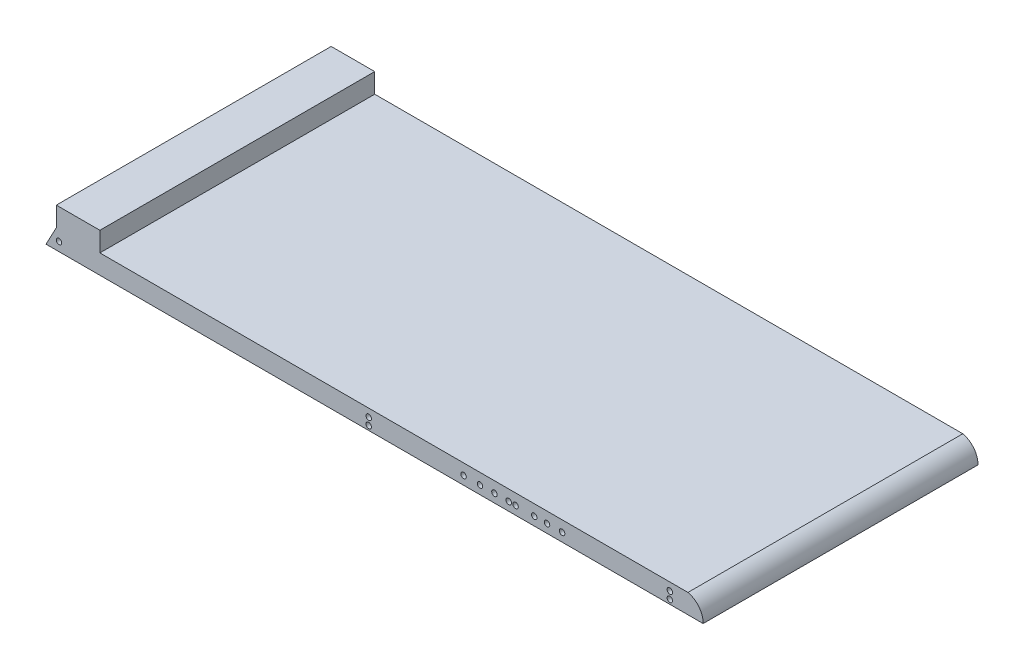
SolidWorks part; units mm, degrees
material "AA380.0-F die"
ref_plane "Front Plane" through (0, 0, 0) normal (0, 0, 1) x (1, 0, 0)
ref_plane "Top Plane" through (0, 0, 0) normal (0, 1, 0) x (1, 0, 0)
ref_plane "Right Plane" through (0, 0, 0) normal (1, 0, 0) x (0, 0, -1)
sketch "Sketch2" plane through (0, 0, 0) normal (0, 0, 1) x (1, 0, 0)
  line L0 (-838, 0) -> (838, 0)
  line L1 (-838, 0) -> (-811.7096, 49.4451)
  line L2 (-811.7096, 49.4451) -> (799.2904, 49.4451)
  arc A1 (838, 0) -> (799.2904, 49.4451) centre (788.0054, 0.7352) ccw
  point P3 (0, 0)
  dimension "D1" = 62
extrude "Boss-Extrude1" add sketch "Sketch2" along normal blind 701
sketch "Sketch3" plane through (0, 0, 701) normal (0, 0, 1) x (1, 0, 0)
  line L0 (838, 0) -> (753, 0)
  line L1 (-838, 0) -> (838, 0) construction
  circle A1 centre (753, 11.0054) radius 7
  circle A2 centre (753, 29.4415) radius 7
  circle A3 centre (-15, 29.4415) radius 7
  circle A4 centre (-15, 11.0054) radius 7
  dimension "D1" = 768
  dimension "D2" = 768
extrude "Cut-Extrude1" cut sketch "Sketch3" against normal blind 14 contours A3 | A4 | A2 | A1
sketch "Sketch4" plane through (0, 0, 0) normal (0, 0, -1) x (-1, 0, 0)
  circle A1 centre (-753, 11) radius 7
  circle A2 centre (-753, 29.4) radius 7
  circle A4 centre (15, 11) radius 7
  circle A6 centre (15, 29.4) radius 7
  dimension "D1" = 18.4
  dimension "D3" = 768
  dimension "D4" = 768
extrude "Cut-Extrude2" cut sketch "Sketch4" against normal blind 14
sketch "Sketch5" plane through (0, 0, 0) normal (0, 0, -1) x (-1, 0, 0)
  circle A0 centre (-320.8661, 24.9474) radius 7
  circle A1 centre (-278.5024, 24.9474) radius 7
extrude "Cut-Extrude3" cut sketch "Sketch5" against normal blind 14
sketch "Sketch6" plane through (0, 0, 0) normal (0, 0, -1) x (-1, 0, 0)
  line L0 (811.7096, 49.4451) -> (838, 0) construction
  circle A0 centre (804.8548, 24.3627) radius 7
  point P4 (824.8548, 24.7225)
  dimension "D1" = 20
extrude "Boss-Extrude2" add sketch "Sketch6" along normal blind 10
sketch "Sketch7" plane through (0, 0, 0) normal (0, 0, -1) x (-1, 0, 0)
  circle A1 centre (-365.5791, 24.9474) radius 7
  circle A2 centre (-405.2746, 24.9474) radius 7
  circle A3 centre (-458.7421, 24.9474) radius 7
  circle A4 centre (-433.6286, 24.9474) radius 7
extrude "Cut-Extrude4" cut sketch "Sketch7" against normal blind 14
sketch "Sketch8" plane through (0, 0, 701) normal (0, 0, 1) x (1, 0, 0)
  circle A0 centre (226.8861, 21.8057) radius 7
  circle A1 centre (268.9181, 21.8057) radius 7
  circle A2 centre (305.7551, 21.8057) radius 7
  circle A3 centre (342.1199, 21.8057) radius 7
  circle A4 centre (407.293, 21.8057) radius 7
  circle A5 centre (439.8192, 21.8057) radius 7
  circle A6 centre (478.175, 21.8057) radius 7
extrude "Cut-Extrude5" cut sketch "Sketch8" against normal blind 14
sketch "Sketch9" plane through (0, 0, 701) normal (0, 0, 1) x (1, 0, 0)
  line L0 (-811.7096, 49.4451) -> (-838, 0) construction
  circle A0 centre (-804.8548, 22.7211) radius 7
  point P4 (-824.8548, 24.7225)
  dimension "D1" = 20
extrude "Cut-Extrude6" cut sketch "Sketch9" against normal blind 14
sketch "Sketch10" plane through (0, 0, 701) normal (0, 0, 1) x (1, 0, 0)
  circle A1 centre (342.1199, 21.8057) radius 7
  circle A2 centre (359.6199, 21.8057) radius 7
  dimension "D1" = 17.5
extrude "Cut-Extrude7" cut sketch "Sketch10" against normal blind 10
sketch "Sketch11" plane through (0, 49.4451, 0) normal (0, 1, 0) x (1, 0, 0)
  line L0 (799.2904, -701) -> (-811.7096, -701) construction
  line L1 (-811.7096, 0) -> (-700.5817, 0)
  line L2 (-811.7096, 0) -> (-811.7096, -701)
  line L3 (-811.7096, -701) -> (-700.5817, -701)
  line L4 (-700.5817, 0) -> (-700.5817, -701)
extrude "Boss-Extrude3" add sketch "Sketch11" along normal blind 50
